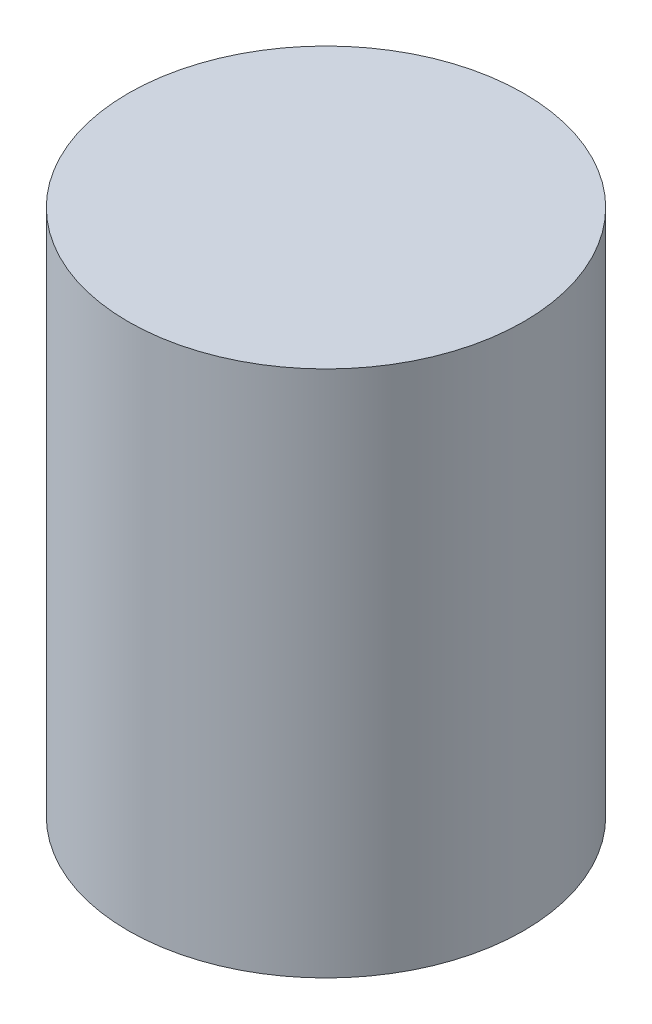
SolidWorks part; units mm, degrees
ref_plane "Front Plane" through (0, 0, 0) normal (0, 0, 1) x (1, 0, 0)
ref_plane "Top Plane" through (0, 0, 0) normal (0, 1, 0) x (1, 0, 0)
ref_plane "Right Plane" through (0, 0, 0) normal (1, 0, 0) x (0, 0, -1)
sketch "Sketch1" plane through (0, 0, 0) normal (0, 1, 0) x (1, 0, 0)
  circle A0 centre (0, 0) radius 38.1
  dimension "D1" = 76.2
extrude "Boss-Extrude1" add sketch "Sketch1" along normal mid plane 101.6
